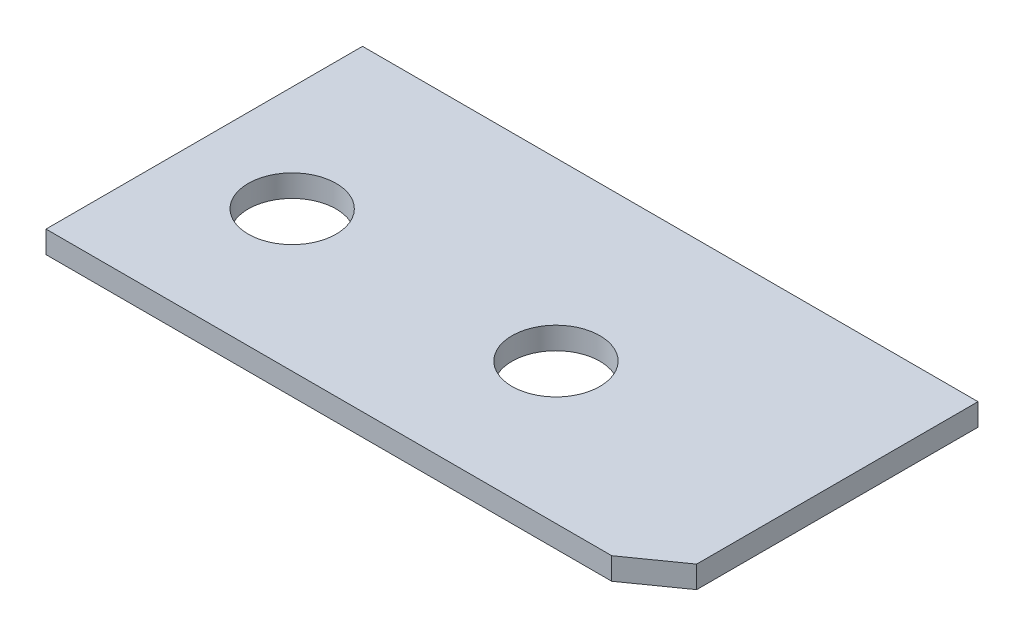
SolidWorks part; units mm, degrees
ref_plane "Plano frontal" through (0, 0, 0) normal (0, 0, 1) x (1, 0, 0)
ref_plane "Plano superior" through (0, 0, 0) normal (0, 1, 0) x (1, 0, 0)
ref_plane "Plano direito" through (0, 0, 0) normal (1, 0, 0) x (0, 0, -1)
sketch "Esboço1" plane through (0, 0, 0) normal (0, 1, 0) x (1, 0, 0)
  line L0 (-17.5, -9) -> (14.6716, -9)
  line L1 (14.6716, -9) -> (17.5, -7)
  line L2 (17.5, -7) -> (17.5, 9)
  line L3 (17.5, 9) -> (-17.5, 9)
  line L4 (-17.5, 9) -> (-17.5, -9)
  circle A0 centre (3.5, -1) radius 2.5
  circle A1 centre (-11.5, -1) radius 2.5
extrude "Ressalto-extrusão1" add sketch "Esboço1" along normal blind 1.26
